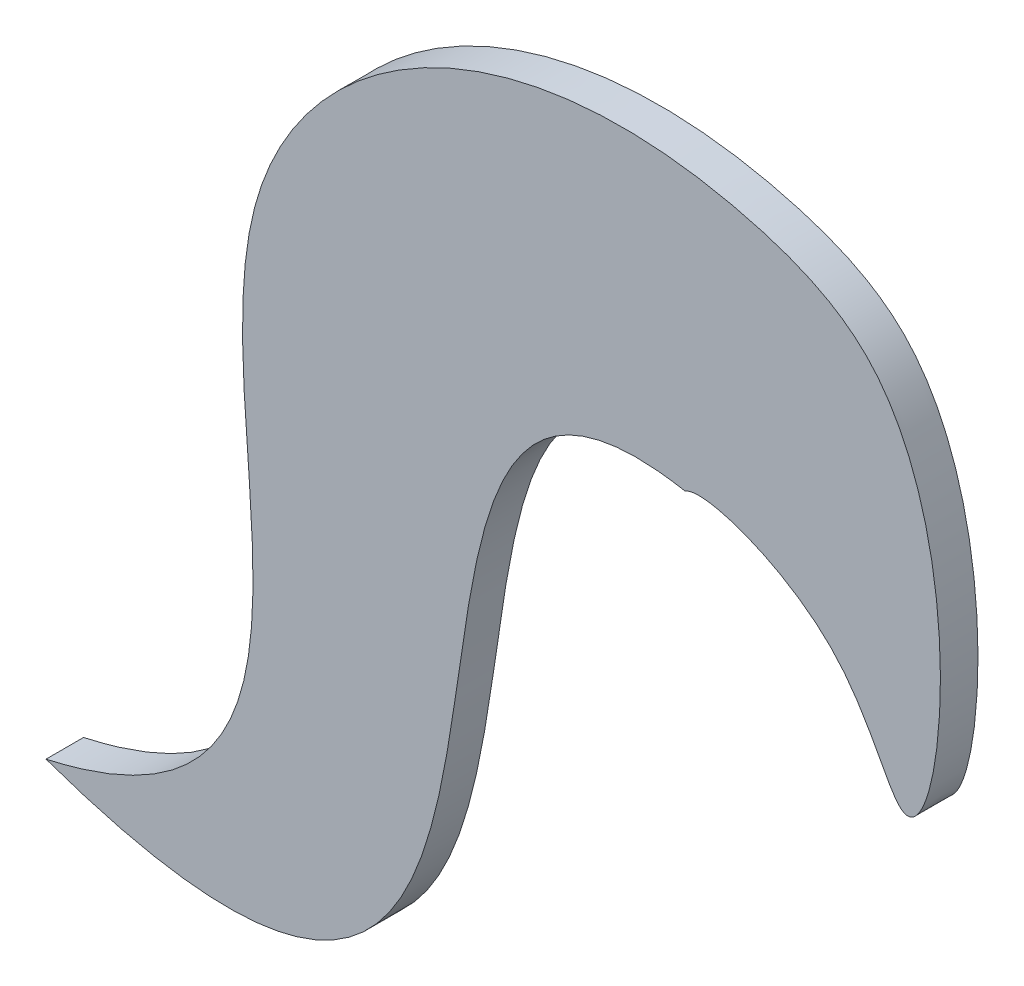
SolidWorks part; units mm, degrees
ref_plane "Alzado" through (0, 0, 0) normal (0, 0, 1) x (1, 0, 0)
ref_plane "Planta" through (0, 0, 0) normal (0, 1, 0) x (1, 0, 0)
ref_plane "Vista lateral" through (0, 0, 0) normal (1, 0, 0) x (0, 0, -1)
sketch "Croquis1" plane through (0, 0, 0) normal (0, 0, 1) x (1, 0, 0)
  spline S0 degree 3 poles (0, 0) (50.6964, -17.8659) (18.2224, 50.1585) (51.0689, 44.0612) knots 0 0 0 0 1 1 1 1
  spline S1 degree 3 poles (0, 0) (26.5497, 5.8743) (0.1524, 48.8361) (40.1296, 72.1443) (74.8492, 58.5218) (70.7451, 20.034) (64.1518, 41.2921) (52.4496, 45.0707) (51.0689, 44.0612) knots 0 0 0 0 0.352432 0.634744 0.68472 0.852189 0.914973 1 1 1 1
  point P4 (0, 0)
extrude "Saliente-Extruir1" add sketch "Croquis1" along normal blind 3
